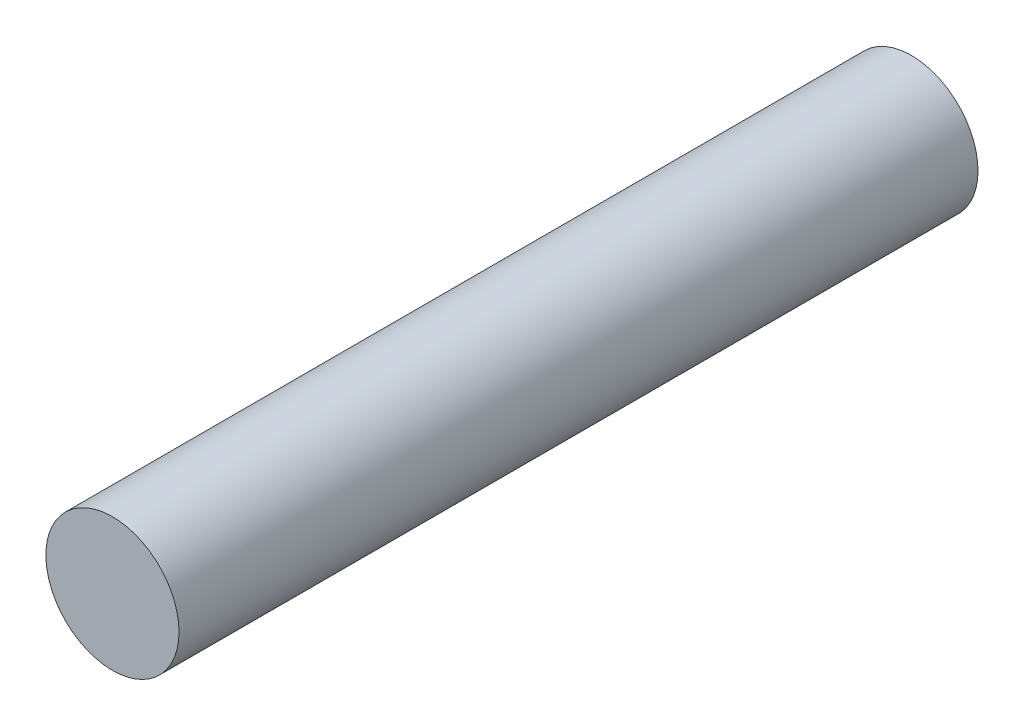
SolidWorks part; units mm, degrees
ref_plane "Front Plane" through (0, 0, 0) normal (0, 0, 1) x (1, 0, 0)
ref_plane "Top Plane" through (0, 0, 0) normal (0, 1, 0) x (1, 0, 0)
ref_plane "Right Plane" through (0, 0, 0) normal (1, 0, 0) x (0, 0, -1)
sketch "Sketch1" plane through (0, 0, 0) normal (0, 0, 1) x (1, 0, 0)
  circle A0 centre (0, 0) radius 2.5
  dimension "D1" = 5
extrude "Boss-Extrude1" add sketch "Sketch1" along normal mid plane 30
